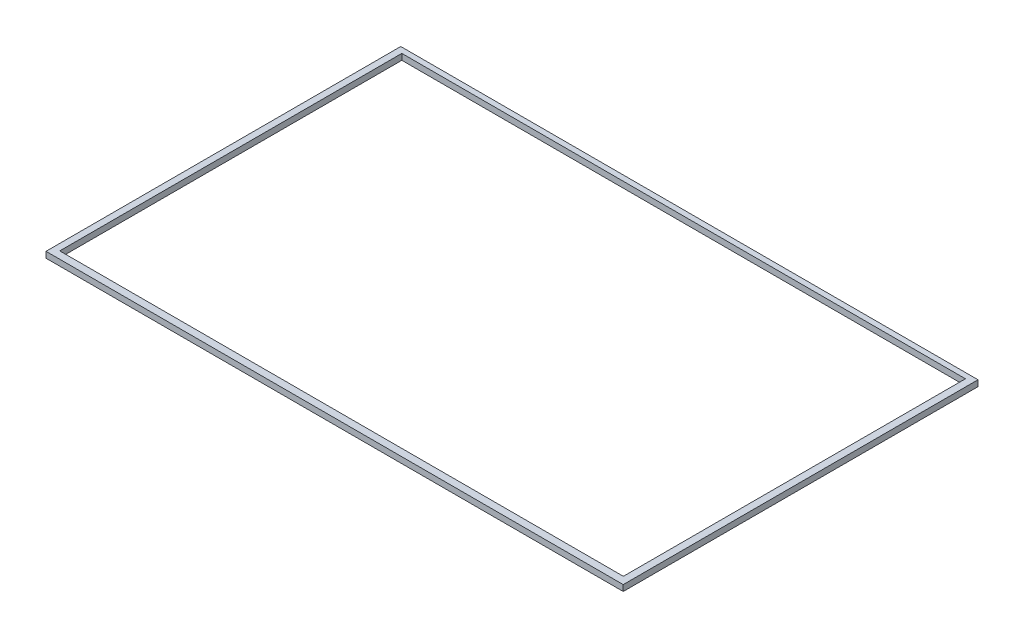
SolidWorks part; units mm, degrees
ref_plane "Front Plane" through (0, 0, 0) normal (0, 0, 1) x (1, 0, 0)
ref_plane "Top Plane" through (0, 0, 0) normal (0, 1, 0) x (1, 0, 0)
ref_plane "Right Plane" through (0, 0, 0) normal (1, 0, 0) x (0, 0, -1)
sketch "Sketch1" plane through (0, 0, 0) normal (0, 1, 0) x (1, 0, 0)
  line L1 (0, 0) -> (152.4, 0)
  line L2 (0, 0) -> (0, 93.6625)
  line L3 (0, 93.6625) -> (152.4, 93.6625)
  line L4 (152.4, 0) -> (152.4, 93.6625)
  line L5 (150.5238, 1.9077) -> (1.7194, 1.9077)
  line L6 (150.5238, 1.9077) -> (150.5238, 92.2252)
  line L7 (150.5238, 92.2252) -> (1.7194, 92.2252)
  line L8 (1.7194, 1.9077) -> (1.7194, 92.2252)
  dimension "D1" = 93.6625
  dimension "D2" = 152.4
extrude "Boss-Extrude1" add sketch "Sketch1" along normal blind 1.5875
